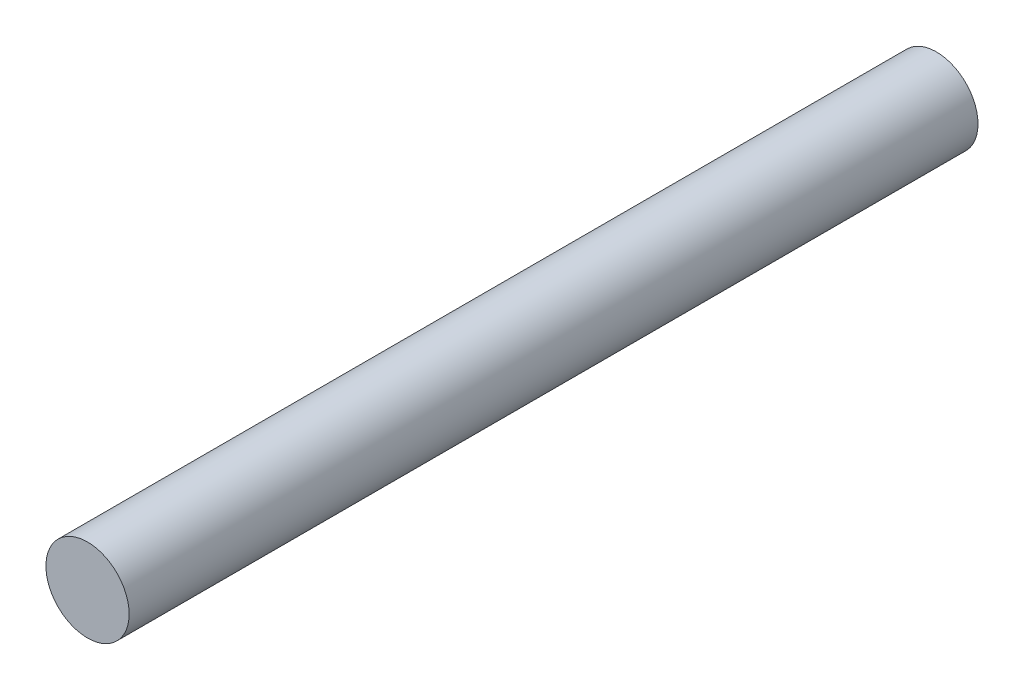
SolidWorks part; units mm, degrees
ref_plane "Front Plane" through (0, 0, 0) normal (1, 0, 0) x (0, 1, 0)
ref_plane "Top Plane" through (0, 0, 0) normal (0, 0, 1) x (0, 1, 0)
ref_plane "Right Plane" through (0, 0, 0) normal (0, 1, 0) x (-1, 0, 0)
sketch "Sketch1" plane through (0, 0, 0) normal (0, 0, 1) x (0, 1, 0)
  circle A0 centre (0, 0) radius 6.223
  dimension "D1" = 12.446
extrude "Boss-Extrude1" add sketch "Sketch1" along normal blind 127
equation "\"Body_OD\" = 3.5in"
equation "\"Body_ID\" = 3.2in"
equation "\"Body_Height\" = 12in"
equation "\"Bearing_OD\" = 1.13in"
equation "\"Bearing_ID\" = 0.5in"
equation "\"Body_Bearing_Hole_OD\" = \"Bearing_OD\" + 0.01in 'with clearance"
equation "\"Pivot_Height\" = 4in 'measured from bottom of tube"
equation "\"Pivot_OD\" = \"Bearing_ID\" - 0.01in 'with clearance"
equation "\"D1@Sketch1\"=\"Pivot_OD\""
